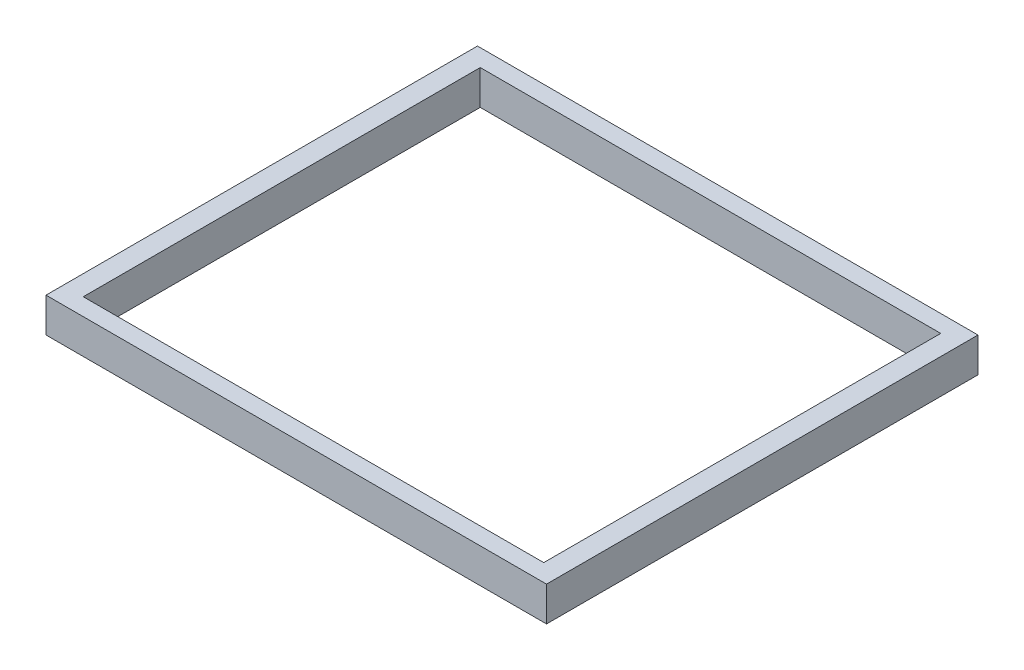
SolidWorks part; units mm, degrees
ref_plane "Front Plane" through (0, 0, 0) normal (0, 0, 1) x (1, 0, 0)
ref_plane "Top Plane" through (0, 0, 0) normal (0, 1, 0) x (1, 0, 0)
ref_plane "Right Plane" through (0, 0, 0) normal (1, 0, 0) x (0, 0, -1)
sketch "Sketch1" plane through (0, 0, 0) normal (0, 1, 0) x (1, 0, 0)
  line L1 (-368.3, -317.5) -> (368.3, -317.5)
  line L2 (-368.3, -317.5) -> (-368.3, 317.5)
  line L3 (-368.3, 317.5) -> (368.3, 317.5)
  line L4 (368.3, -317.5) -> (368.3, 317.5)
  line L5 (-368.3, -317.5) -> (368.3, 317.5) construction
  line L6 (-368.3, 317.5) -> (368.3, -317.5) construction
  line L7 (-338.836, -292.1) -> (338.836, -292.1)
  line L8 (-338.836, -292.1) -> (-338.836, 292.1)
  line L9 (-338.836, 292.1) -> (338.836, 292.1)
  line L10 (338.836, -292.1) -> (338.836, 292.1)
  line L11 (-338.836, -292.1) -> (338.836, 292.1) construction
  line L12 (-338.836, 292.1) -> (338.836, -292.1) construction
  point P0 (0, 0)
  point P6 (0, 0)
  dimension "D1" = 635
  dimension "D2" = 736.6
  dimension "D3" = 25.4
extrude "Boss-Extrude2" add sketch "Sketch1" along normal blind 50.8
